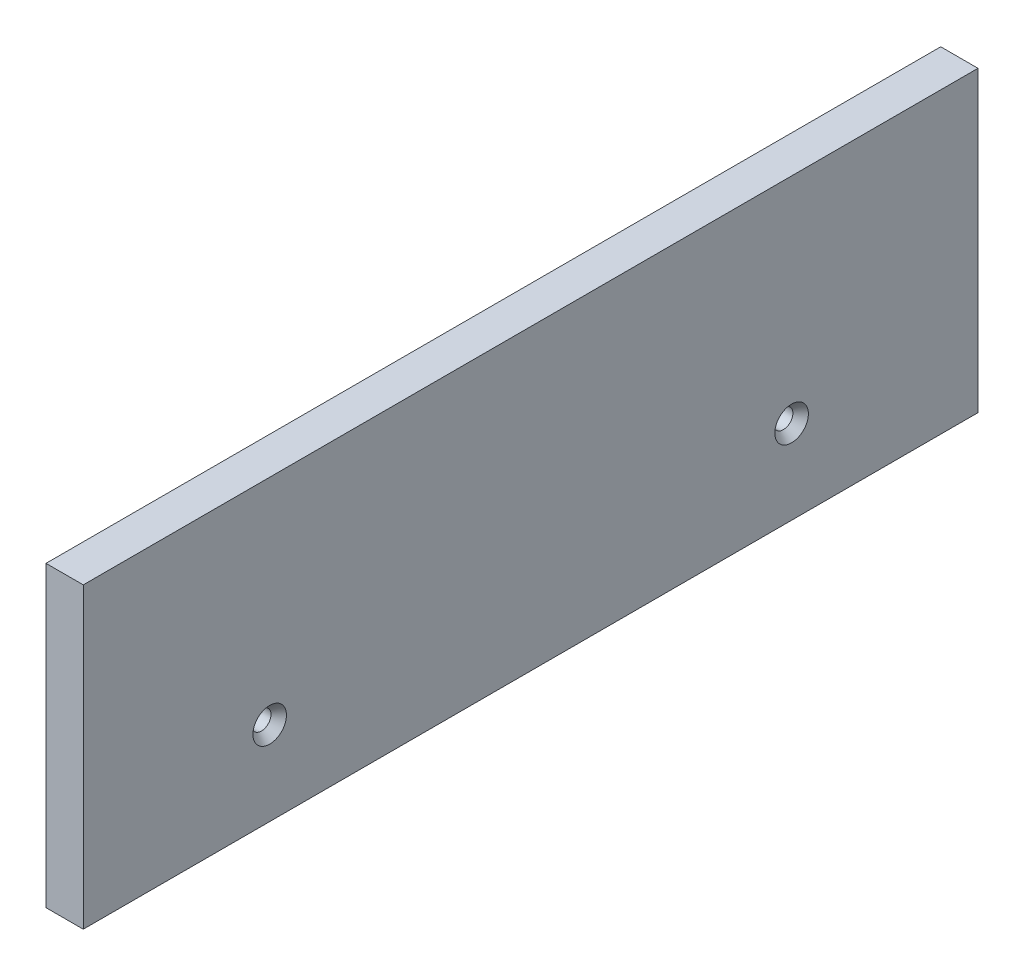
SolidWorks part; units mm, degrees
ref_plane "Front Plane" through (0, 0, 0) normal (0, 0, 1) x (1, 0, 0)
ref_plane "Top Plane" through (0, 0, 0) normal (0, 1, 0) x (1, 0, 0)
ref_plane "Right Plane" through (0, 0, 0) normal (1, 0, 0) x (0, 0, -1)
sketch "Sketch1" plane through (0, 0, 0) normal (1, 0, 0) x (0, 0, -1)
  line L1 (0, 0) -> (152.4, 0)
  line L2 (0, 0) -> (0, 50.8)
  line L3 (0, 50.8) -> (152.4, 50.8)
  line L4 (152.4, 0) -> (152.4, 50.8)
  dimension "D1" = 50.8
  dimension "D2" = 152.4
extrude "Boss-Extrude1" add sketch "Sketch1" along normal blind 6.35
hole_wizard "CSK for #4 Flat Head Machine Screw1" positions "Sketch3" profile "Sketch2" countersink size "#4" standard "ANSI Inch" end condition through all
sketch "Sketch3" plane through (6.35, 0, 0) normal (1, 0, 0) x (0, 0, -1)
  line L0 (0, 50.8) -> (0, 0) construction
  line L2 (152.4, 0) -> (152.4, 50.8) construction
  line L3 (0, 0) -> (152.4, 0) construction
  point P0 (31.75, 14.2875)
  point P2 (120.65, 14.2875)
  dimension "D1" = 31.75
  dimension "D2" = 14.2875
  dimension "D3" = 31.75
  dimension "D4" = 14.2875
sketch "Sketch2" plane through (6.35, 14.2875, -31.75) normal (0, 1, 0) x (0, 0, -1)
  line L0 (0, 0) -> (0, 6.35)
  line L1 (0, 6.35) -> (1.6319, 6.35)
  line L2 (1.6319, 6.35) -> (1.6319, 1.4098)
  line L3 (1.6319, 1.4098) -> (2.8575, 0)
  line L5 (2.8575, 0) -> (0, 0)
  line L6 (-1.6319, 1.4098) -> (-2.8575, 0) construction
  line L11 (0, -6.35) -> (0, 107.95) construction
  dimension "Thru Hole Dia." = 3.2639
  dimension "Thru Hole Depth" = 6.35
  dimension "Near C'Sink Dia." = 5.715
  dimension "Near C'Sink Angle" = 82
